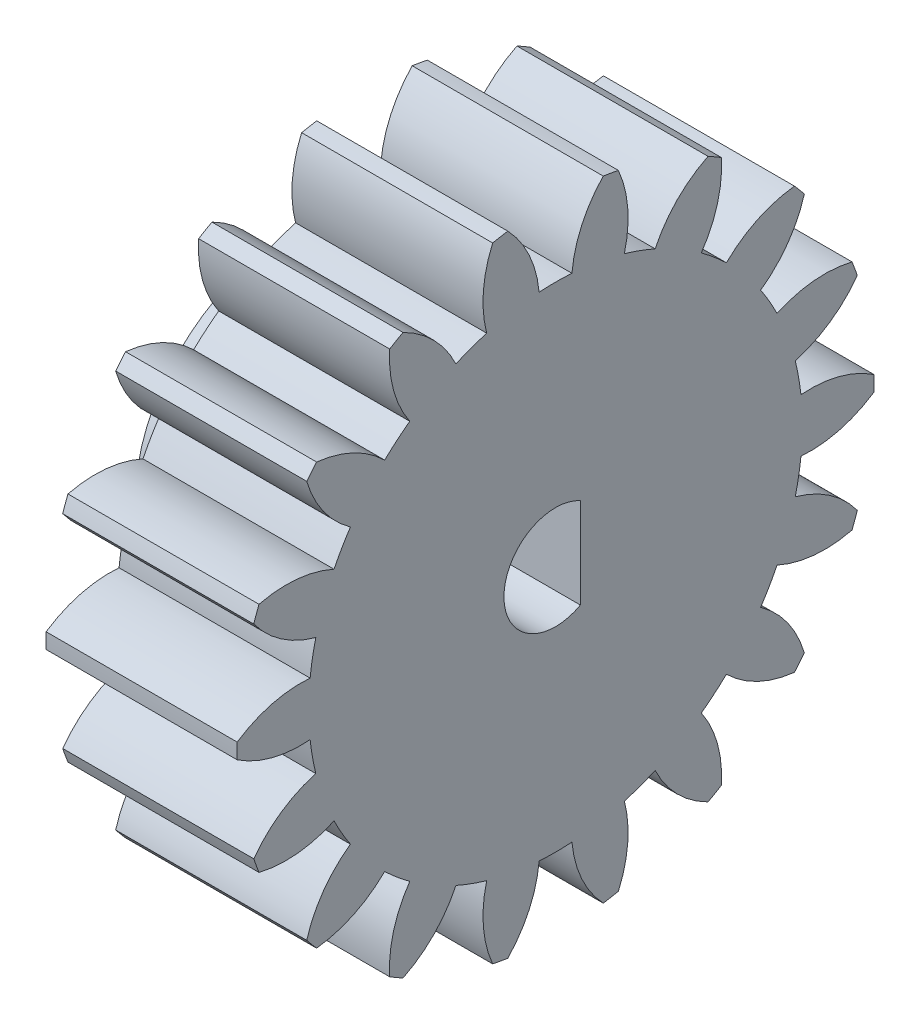
SolidWorks part; units mm, degrees
ref_plane "Plane1" through (0, 0, 0) normal (0, 0, 1) x (1, 0, 0)
ref_plane "Plane2" through (0, 0, 0) normal (0, 1, 0) x (1, 0, 0)
ref_plane "Plane3" through (0, 0, 0) normal (1, 0, 0) x (0, 0, -1)
other "Configuration Table"
sketch "HoldingSke" plane through (0, 0, 0) normal (0, 1, 0) x (1, 0, 0)
  line L0 (0, 0) -> (579.7641, -188.3768)
  line L1 (-15, 0) -> (100, 0) construction
  line L2 (0, 0) -> (-2.1039, 2.3779)
  line L3 (0, 0) -> (-11.863, 4.5341)
  line L4 (0, 0) -> (8.2133, 2.6687)
  line L5 (0, 0) -> (-47.5972, -17.7524)
  line L6 (0, 0) -> (-5.2639, -3.5516)
  line L7 (-2.1039, 2.3779) -> (8.8308, 51.9871)
  line L8 (-76.2, 54.61) -> (-75.184, 54.61)
  line L9 (-71.009, 38.7566) -> (-53.1078, 45.2721)
  line L10 (-76.2, 71.12) -> (104.1128, 71.12)
  line L11 (0, 0) -> (-6.35, 0)
  line L12 (-76.2, 101.6) -> (-76.1573, 101.6)
  line L13 (24.9733, 27.94) -> (52.9518, 28.4284)
  line L14 (24.9733, 27.94) -> (25.0241, 27.9398)
  line L15 (24.9733, 27.94) -> (100.4021, 29.52)
  circle A0 centre (0, 0) radius 0.3969
  circle A1 centre (0, 0) radius 8.2042
  circle A2 centre (0, 0) radius 38.1
  circle A3 centre (0, 0) radius 0.3969
  dimension "MHD" = 16.4084
  dimension "Hub_dia" = 76.2
  dimension "Bore" = 0.7937
  dimension "MBD" = 0.7937
  dimension "Num_teeth" = 18
  dimension "Pitch" = 609.6
  dimension "Overall_len" = 50.8
  dimension "Show_teeth" = 18
  dimension "Thickness" = 6.35
  dimension "OAL" = 50.8001
  dimension "T_dim" = 1.016
  dimension "Ap" = 20
  dimension "H" = 19.05
  dimension "Pitch_radius" = 180.3128
  dimension "Backlash" = 0.0427
  dimension "Addendum_fac" = 1
  dimension "Dedendum_fac" = 1.2
  dimension "Clearance_fac" = 0.2
  dimension "Dedendum_add" = 0.0508
sketch "BasProSke" plane through (0, 0, 0) normal (0, 1, 0) x (1, 0, 0)
  line L0 (-10, 0) -> (60, 0) construction
  line L1 (0, 0) -> (0, 10.5833)
  line L2 (0, 0) -> (6.35, 0)
  line L3 (6.35, 0) -> (6.35, 10.5833)
  line L4 (6.35, 10.5833) -> (0, 10.5833)
  dimension "Thickness" = 6.35
  dimension "Diameter" = 21.1667
revolve "Base-Revolve" add sketch "BasProSke" angle 360 about L0
sketch "TooCutSke" plane through (0, 0, 0) normal (1, 0, 0) x (0, 0, -1)
  line L1 (0, 0) -> (0, 107) construction
  line L2 (0, 0) -> (-0.9048, 9.4819) construction
  line L3 (0, 0) -> (-3.2976, 18.7015) construction
  line L4 (-0.9048, 9.4819) -> (-1.6488, 9.3507) construction
  arc A0 (0.5444, 8.1861) -> (-0.5444, 8.1861) centre (0, 0) ccw
  arc A1 (1.6071, 10.4863) -> (-1.6071, 10.4863) centre (0, 0) ccw
  circle A2 centre (0, 0) radius 9.525 construction
  circle A3 centre (0, 0) radius 8.9506 construction
  arc A4 (-0.5444, 8.1861) -> (-1.6071, 10.4863) centre (-4.3377, 7.8293) ccw
  arc A5 (1.6071, 10.4863) -> (0.5444, 8.1861) centre (4.3377, 7.8293) ccw
  dimension "Root_dia" = 16.4084
  dimension "Overcut_dia" = 21.2175
  dimension "Pitch_dia" = 19.05
  dimension "Base_dia" = 17.9011
  dimension "Flank_rad" = 3.81
  dimension "Half_ang" = 10
  dimension "Half_CT" = 0.7555
extrude "ToothCut" cut sketch "TooCutSke" along normal through all
fillet "Breaks" [suppressed] radius 0.0212
fillet "RootFillets" [suppressed] radius 0.2625
pattern_circular "TeethCuts" count 18 every 20 about axis through (-10, 0, 0) along (1, 0, 0) of "ToothCut", "RootFillets", "Breaks"
sketch "HubNeaOneSke" plane through (0, 0, 0) normal (-1, 0, 0) x (0, 0, 1)
  circle A0 centre (0, 0) radius 8.2042
  dimension "Diameter" = 16.4084
extrude "HubNearOne" [suppressed] add sketch "HubNeaOneSke" along normal blind 44.4501
sketch "HubNeaBotSke" plane through (0, 0, 0) normal (-1, 0, 0) x (0, 0, 1)
  circle A0 centre (0, 0) radius 8.2042
  dimension "Diameter" = 16.4084
extrude "HubNearBoth" [suppressed] add sketch "HubNeaBotSke" along normal blind 22.225
ref_plane "FarPln" through (6.35, 0, 0) normal (1, 0, 0) x (0, 0, -1)
sketch "HubFarSke" plane through (6.35, 0, 0) normal (1, 0, 0) x (0, 0, -1)
  circle A0 centre (0, 0) radius 8.2042
  dimension "Diameter" = 16.4084
extrude "HubFar" [suppressed] add sketch "HubFarSke" along normal blind 22.225
sketch "BorSke" plane through (0, 0, 0) normal (1, 0, 0) x (0, 0, -1)
  circle A0 centre (0, 0) radius 0.3969
  dimension "Diameter" = 0.7937
extrude "Bore" cut sketch "BorSke" along normal mid plane 101.6001
sketch "KeySke" plane through (0, 0, 0) normal (1, 0, 0) x (0, 0, -1)
  line L0 (-0.127, 0) -> (-0.127, 0.6191)
  line L1 (-0.127, 0.6191) -> (0.127, 0.6191)
  line L2 (0.127, 0.6191) -> (0.127, 0)
  line L3 (0, 0) -> (0, 34) construction
  line L4 (-0.127, 0) -> (0.127, 0)
  dimension "Offset" = 0.6191
extrude "Keyway" [suppressed] cut sketch "KeySke" along normal mid plane 101.6001
pattern_circular "Keyway2" [suppressed] count 2 every 90 about axis through (-10, 0, 0) along (1, 0, 0)
sketch "Sketch1" plane through (6.35, 0, 0) normal (1, 0, 0) x (0, 0, -1)
  line L0 (0.8255, -1.5027) -> (0.8255, 1.5027)
  line L1 (-1.7145, 2.8993) -> (-1.7145, -2.3273) construction
  arc A0 (0.8255, 1.5027) -> (0.8255, -1.5027) centre (0, 0) ccw
  point P7 (0.889, 1.3912)
  dimension "D1" = 3.429
  dimension "D2" = 2.54
extrude "Cut-Extrude1" cut sketch "Sketch1" against normal through all
sketch "Sketch2" plane through (0, 0, 0) normal (-1, 0, 0) x (0, 0, 1)
  circle A0 centre (0, 0) radius 5.08
  dimension "D1" = 10.16
extrude "Boss-Extrude1" add sketch "Sketch2" along normal blind 2.54
sketch "Sketch3" plane through (-2.54, 0, 0) normal (-1, 0, 0) x (0, 0, 1)
  circle A0 centre (0, 0) radius 2.032
  dimension "D1" = 4.064
extrude "Cut-Extrude2" cut sketch "Sketch3" against normal blind 2.0066
equation "' \"Pitch@HoldingSke\" = 4"
equation "' \"Num_teeth@HoldingSke\" = 12"
equation "' \"Ap@HoldingSke\" =  20"
equation "' \"Ap@HoldingSke\" = 20"
equation "' \"Width@HoldingSke\" = 0.5"
equation "' \"Hub_dia@HoldingSke\"= 1"
equation "' \"Hub_dia@HoldingSke\" = 1"
equation "' \"Overall_len@HoldingSke\" = 1.0"
equation "' \"Bore@HoldingSke\" = 0.75"
equation "' \"T_dim@HoldingSke\" = 0.85"
equation "' \"Width@KeySke\" = 0.25"
equation "' \"Show_teeth@HoldingSke\" = 13"
equation "' \"Backlash@HoldingSke\" = 0.009"
equation "' \"Addendum_fac@HoldingSke\" = 1.0"
equation "' \"Dedendum_fac@HoldingSke\" = 1.25"
equation "' \"Dedendum_add@HoldingSke\" = 0.00005"
equation "' \"Clearance_fac@HoldingSke\" = 0.25"
equation "' \"Pitch@HoldingSke\" = 0.5"
equation "' \"Num_teeth@HoldingSke\" = 23"
equation "' \"Show_teeth@HoldingSke\" = 23"
equation "' \"Backlash@HoldingSke\" = 0.0375"
equation "\"Overcut_dia@TooCutSke\" = (\"Num_teeth@HoldingSke\" + 2 * \"Addendum_fac@HoldingSke\") / \"Pitch@HoldingSke\" + 0.002"
equation "\"Pitch_dia@TooCutSke\" = \"Num_teeth@HoldingSke\" / \"Pitch@HoldingSke\""
equation "\"Base_dia@TooCutSke\" = \"Num_teeth@HoldingSke\" / \"Pitch@HoldingSke\" * cos((\"Ap@HoldingSke\"  * 3.14159265 / 180))"
equation "\"Root_dia@TooCutSke\" = (\"Num_teeth@HoldingSke\" + 2) / \"Pitch@HoldingSke\" - 2 * (\"Addendum_fac@HoldingSke\" + \"Dedendum_fac@HoldingSke\") / \"Pitch@HoldingSke\" - \"Dedendum_add@HoldingSke\" * 2"
equation "\"Half_ang@TooCutSke\" = 180 / \"Num_teeth@HoldingSke\""
equation "\"Half_CT@TooCutSke\" = \"Num_teeth@HoldingSke\" / \"Pitch@HoldingSke\" * sin((3.14159265 / 2 / \"Num_teeth@HoldingSke\")) / 2 - 7 * \"Backlash@HoldingSke\" / 4"
equation "\"Flank_rad@TooCutSke\" = \"Num_teeth@HoldingSke\" / \"Pitch@HoldingSke\" / 5"
equation "\"Radius@RootFillets\" = \"Clearance_fac@HoldingSke\" / \"Pitch@HoldingSke\" + \"Dedendum_add@HoldingSke\""
equation "\"Break_rad@Breaks\" = 0.02 / \"Pitch@HoldingSke\""
equation "\"Thickness@HoldingSke\" = \"Width@HoldingSke\""
equation "\"OAL@HoldingSke\" = \"Thickness@HoldingSke\""
equation "\"MHD@HoldingSke\" = (\"Num_teeth@HoldingSke\" + 2) / \"Pitch@HoldingSke\" - 2 * (\"Addendum_fac@HoldingSke\" + \"Dedendum_fac@HoldingSke\")  / \"Pitch@HoldingSke\" - \"Dedendum_add@HoldingSke\" * 2"
equation "\"MBD@HoldingSke\" = (\"Num_teeth@HoldingSke\" + 2) / \"Pitch@HoldingSke\" - 2 * (\"Addendum_fac@HoldingSke\" + \"Dedendum_fac@HoldingSke\")  / \"Pitch@HoldingSke\" - \"Dedendum_add@HoldingSke\" * 2 - 0.002"
equation "\"MHD@HoldingSke\" = ((sgn( \"MHD@HoldingSke\" - \"Hub_dia@HoldingSke\" )-1)*( \"MHD@HoldingSke\" - \"Hub_dia@HoldingSke\" ))/-2+ \"Hub_dia@HoldingSke\""
equation "\"MBD@HoldingSke\" = ((sgn( \"MBD@HoldingSke\" - \"Bore@HoldingSke\" )-1)*( \"MBD@HoldingSke\" - \"Bore@HoldingSke\" ))/-2+ \"Bore@HoldingSke\""
equation "\"OAL@HoldingSke\" = ((sgn( \"OAL@HoldingSke\" - \"Overall_len@HoldingSke\" )+1)*( \"OAL@HoldingSke\" - \"Overall_len@HoldingSke\" ))/2 + \"Overall_len@HoldingSke\" + 0.000002"
equation "\"Num_teeth@TeethCuts\" = int( \"Show_teeth@HoldingSke\" ) + 1"
equation "\"Num_teeth@TeethCuts\" = ((sgn( \"Num_teeth@TeethCuts\" - \"Num_teeth@HoldingSke\" )-1)*( \"Num_teeth@TeethCuts\" - \"Num_teeth@HoldingSke\" ))/-2+ \"Num_teeth@HoldingSke\""
equation "\"Num_teeth@TeethCuts\" = ((sgn( \"Num_teeth@TeethCuts\" - 2.0)+1)*( \"Num_teeth@TeethCuts\" - 2.0))/2 +2.0"
equation "\"Angle@TeethCuts\" = 360.0 / \"Num_teeth@HoldingSke\""
equation "\"Diameter@BasProSke\" = (\"Num_teeth@HoldingSke\" + 2 * \"Addendum_fac@HoldingSke\") / \"Pitch@HoldingSke\""
equation "\"Thickness@BasProSke\"  = \"Thickness@HoldingSke\""
equation "' \"Fillet_rad@BasProSke\" =  \"Thickness@HoldingSke\" * 0.05"
equation "' \"Fillet_rad@BasProSke\" = \"Thickness@HoldingSke\" * 0.05"
equation "\"MHD@HoldingSke\" = ((sgn( \"MHD@HoldingSke\" - \"Root_dia@TooCutSke\" )-1)*( \"MHD@HoldingSke\" - \"Root_dia@TooCutSke\" ))/-2+ \"Root_dia@TooCutSke\""
equation "\"Diameter@HubNeaOneSke\" = \"MHD@HoldingSke\""
equation "\"Length@HubNearOne\" = \"OAL@HoldingSke\" - \"Thickness@BasProSke\""
equation "\"Diameter@HubNeaBotSke\" = \"MHD@HoldingSke\""
equation "\"Length@HubNearBoth\" = ( \"OAL@HoldingSke\" - \"Thickness@BasProSke\" ) / 2.0"
equation "\"Thickness@FarPln\" = \"Thickness@BasProSke\""
equation "\"Diameter@HubFarSke\" = \"MHD@HoldingSke\""
equation "\"Length@HubFar\" = ( \"OAL@HoldingSke\" - \"Thickness@BasProSke\" ) / 2.0"
equation "\"Diameter@BorSke\" = \"MBD@HoldingSke\""
equation "\"D1@Bore\" = \"OAL@HoldingSke\" * 2.0"
equation "\"D1@Keyway\" = \"OAL@HoldingSke\" * 2.0"
equation "\"Offset@KeySke\" = \"T_dim@HoldingSke\" - \"MBD@HoldingSke\" / 2.0"
